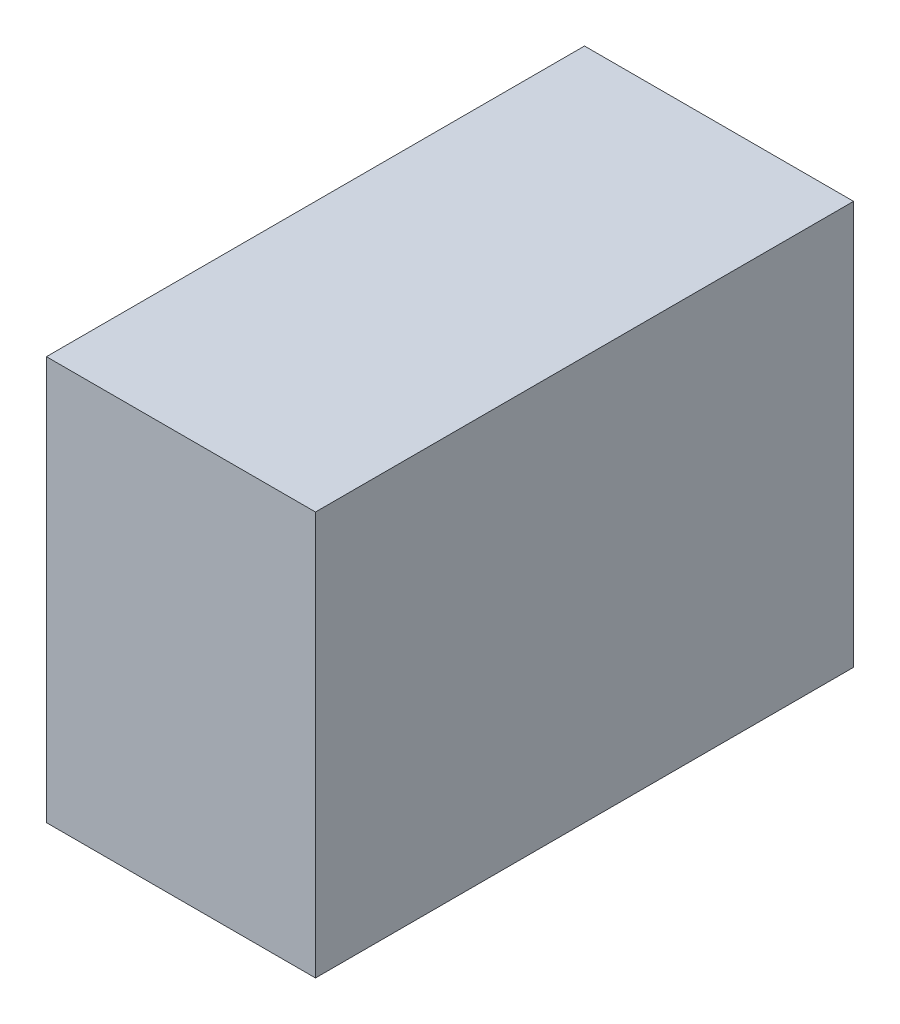
SolidWorks part; units mm, degrees
ref_plane "Front Plane" through (0, 0, 0) normal (0, 0, 1) x (1, 0, 0)
ref_plane "Top Plane" through (0, 0, 0) normal (0, 1, 0) x (1, 0, 0)
ref_plane "Right Plane" through (0, 0, 0) normal (1, 0, 0) x (0, 0, -1)
ref_plane "plane:corpus-xy" through (0, 0, 0) normal (0, 0, 1) x (1, 0, 0)
sketch "sketch:main-profile" plane through (0, 0, 0) normal (0, 0, 1) x (1, 0, 0)
  line L0 (0, 0) -> (20, 0)
  line L1 (20, 0) -> (20, 30)
  line L2 (20, 30) -> (0, 30)
  line L3 (0, 30) -> (0, 0)
extrude "feature:block" add sketch "sketch:main-profile" along normal blind 40 separate body
